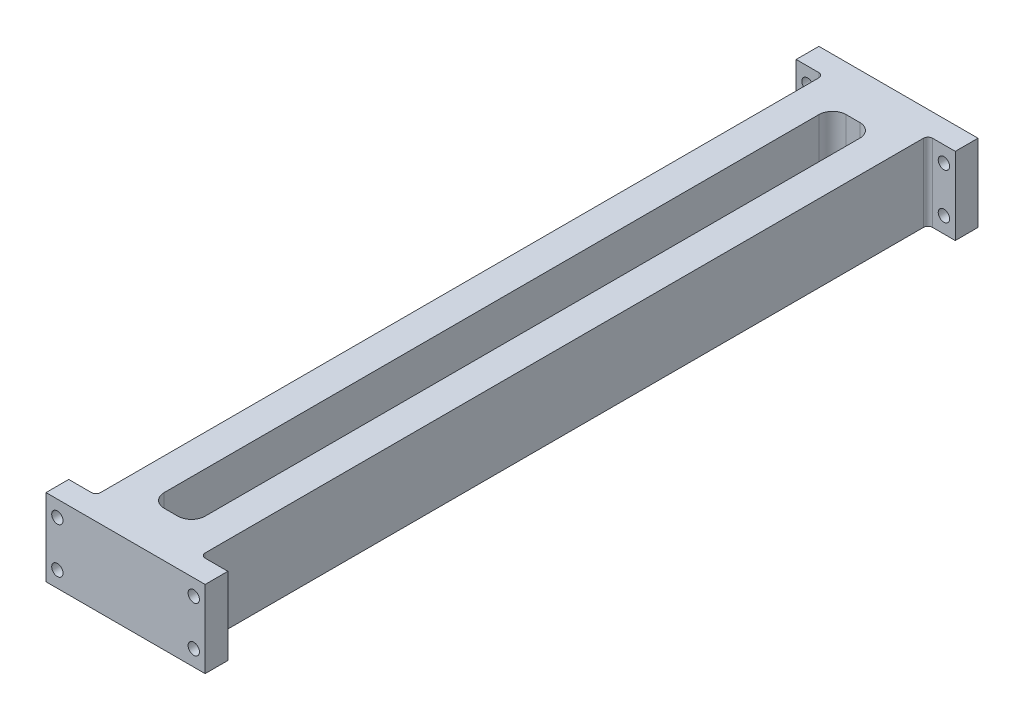
SolidWorks part; units mm, degrees
material "PLA"
ref_plane "Front Plane" through (0, 0, 0) normal (0, 0, 1) x (1, 0, 0)
ref_plane "Top Plane" through (0, 0, 0) normal (0, 1, 0) x (1, 0, 0)
ref_plane "Right Plane" through (0, 0, 0) normal (1, 0, 0) x (0, 0, -1)
sketch "Sketch1" plane through (0, 0, 0) normal (0, 0, 1) x (1, 0, 0)
  line L0 (14.605, 10.795) -> (-14.605, 10.795)
  line L1 (-14.605, 10.795) -> (-14.605, -10.795)
  line L2 (0, 10.795) -> (0, 0) construction
  line L3 (14.605, 0) -> (-14.605, 0) construction
  line L4 (-14.605, -10.795) -> (14.605, -10.795)
  line L5 (14.605, 10.795) -> (14.605, -10.795)
  point P10 (0, -10.795)
  dimension "D1" = 21.59
  dimension "D2" = 29.21
extrude "Boss-Extrude1" add sketch "Sketch1" along normal mid plane 203.2
sketch "Sketch2" plane through (0, 0, 101.6) normal (0, 0, 1) x (1, 0, 0)
  line L0 (-22.225, 10.795) -> (22.225, 10.795)
  line L1 (22.225, 10.795) -> (22.225, -10.795)
  line L2 (-22.225, 10.795) -> (-22.225, -10.795)
  line L3 (0, 10.795) -> (0, 0) construction
  line L4 (-22.225, 0) -> (0, 0) construction
  line L5 (-22.225, -10.795) -> (22.225, -10.795)
  circle A0 centre (-19.05, 6.35) radius 1.5875
  circle A1 centre (-19.05, -6.35) radius 1.5875
  circle A2 centre (19.05, -6.35) radius 1.5875
  circle A3 centre (19.05, 6.35) radius 1.5875
  point P8 (22.225, 0)
  dimension "D5" = 3.175
  dimension "D1" = 44.45
  dimension "D2" = 21.59
  dimension "D3" = 38.1
  dimension "D4" = 12.7
extrude "Boss-Extrude2" add sketch "Sketch2" along normal blind 6.35
mirror "Mirror1" about plane through (0, 0, 0) normal (0, 0, 1) of "Boss-Extrude2"
fillet "Fillet1" radius 1.27 4 edges at (14.605, 0, -101.6) (-14.605, 0, -101.6) (-14.605, 0, 101.6) (14.605, 0, 101.6)
sketch "Sketch3" plane through (0, 10.795, 0) normal (0, 1, 0) x (1, 0, 0)
  line L0 (-5.715, -95.25) -> (-5.715, 95.25)
  line L1 (-5.715, 95.25) -> (5.715, 95.25)
  line L2 (5.715, 95.25) -> (5.715, -95.25)
  line L3 (-14.605, -100.33) -> (-14.605, 100.33) construction
  line L4 (14.605, -100.33) -> (14.605, 100.33) construction
  line L5 (22.225, 107.95) -> (-22.225, 107.95) construction
  line L6 (-5.715, 0) -> (5.715, 0) construction
  line L7 (-5.715, -95.25) -> (5.715, -95.25)
  dimension "D1" = 8.89
  dimension "D2" = 8.89
  dimension "D3" = 12.7
extrude "Cut-Extrude1" cut sketch "Sketch3" against normal through all
fillet "Fillet2" radius 3.81 4 edges at (5.715, 0, 95.25) (-5.715, 0, 95.25) (5.715, 0, -95.25) (-5.715, 0, -95.25)
